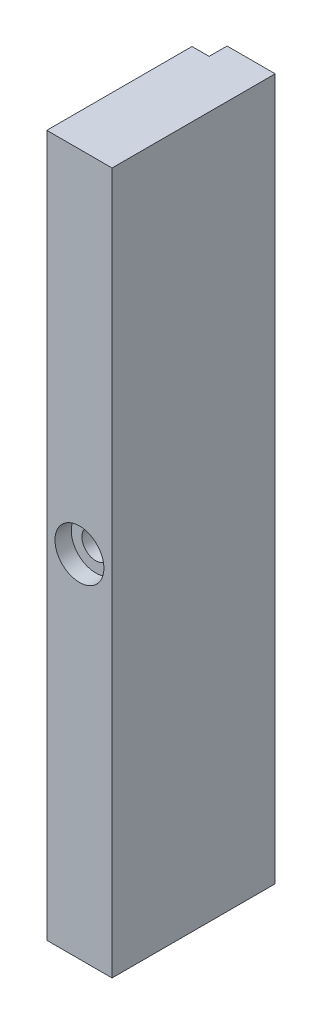
SolidWorks part; units mm, degrees
other "Ballast End Stop Rear"
ref_plane "Front Plane" through (0, 0, 0) normal (0, 0, 1) x (1, 0, 0)
ref_plane "Top Plane" through (0, 0, 0) normal (0, 1, 0) x (1, 0, 0)
ref_plane "Right Plane" through (0, 0, 0) normal (1, 0, 0) x (0, 0, -1)
sketch3d "Main Profile Sketch datum points"
  point P0 (0, 0, 140)
  point P1 (10, 0, 140)
  point P2 (0, 10, 140)
ref_plane "Main Profile Sketch plane" through (0, 0, 140) normal (0, 0, 1) x (1, 0, 0)
sketch "Main Profile Sketch" plane through (0, 0, 140) normal (0, 0, 1) x (1, 0, 0)
  line L0 (-155.5, 43) -> (-147.5, 43)
  line L1 (-147.5, 43) -> (-147.5, -43)
  line L2 (-155.5, -43) -> (-147.5, -43)
  line L3 (-155.5, 43) -> (-155.5, -43)
  circle A0 centre (-151.5, 0) radius 3
extrude "Main Extrusion" add sketch "Main Profile Sketch" against normal blind 2 separate body
sketch3d "Detail Profile 2 Sketch datum points"
  point P0 (0, 0, 138)
  point P1 (10, 0, 138)
  point P2 (0, 10, 138)
ref_plane "Detail Profile 2 Sketch plane" through (0, 0, 138) normal (0, 0, 1) x (1, 0, 0)
sketch "Detail Profile 2 Sketch" plane through (0, 0, 138) normal (0, 0, 1) x (1, 0, 0)
  line L0 (-155.5, 43) -> (-147.5, 43)
  line L1 (-147.5, 43) -> (-147.5, -43)
  line L2 (-155.5, -43) -> (-147.5, -43)
  line L3 (-155.5, 43) -> (-155.5, -43)
  circle A0 centre (-151.5, 0) radius 1.7
extrude "Detail Extrusion 2" add sketch "Detail Profile 2 Sketch" against normal blind 15.8
sketch3d "Detail Profile 3 Sketch datum points"
  point P0 (0, 0, 122.2)
  point P1 (10, 0, 122.2)
  point P2 (0, 10, 122.2)
ref_plane "Detail Profile 3 Sketch plane" through (0, 0, 122.2) normal (0, 0, 1) x (1, 0, 0)
sketch "Detail Profile 3 Sketch" plane through (0, 0, 122.2) normal (0, 0, 1) x (1, 0, 0)
  line L0 (-153.4, 43) -> (-153.4, -43)
  line L1 (-153.4, 43) -> (-147.5, 43)
  line L2 (-147.5, 43) -> (-147.5, -43)
  line L3 (-153.4, -43) -> (-147.5, -43)
  circle A0 centre (-151.5, 0) radius 1.7
extrude "Detail Extrusion 3" add sketch "Detail Profile 3 Sketch" against normal blind 2.2
